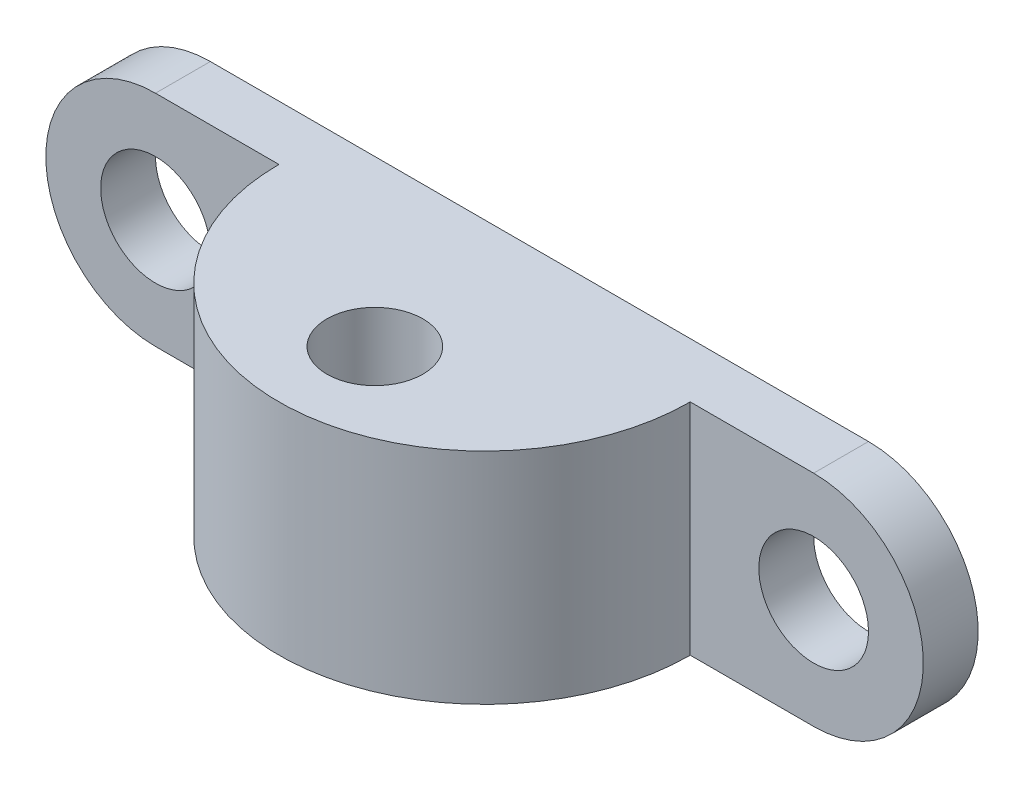
SolidWorks part; units mm, degrees
ref_plane "Front Plane" through (0, 0, 0) normal (0, 0, 1) x (1, 0, 0)
ref_plane "Top Plane" through (0, 0, 0) normal (0, 1, 0) x (1, 0, 0)
ref_plane "Right Plane" through (0, 0, 0) normal (1, 0, 0) x (0, 0, -1)
sketch "Sketch1" plane through (0, 0, 0) normal (0, 0, 1) x (1, 0, 0)
  line L1 (0, 4) -> (24, 4)
  line L2 (0, 4) -> (0, -4)
  line L3 (0, -4) -> (24, -4)
  line L4 (24, 4) -> (24, -4)
  circle A0 centre (0, 0) radius 4
  circle A1 centre (24, 0) radius 4
  dimension "D2" = 8
  dimension "D1" = 24
extrude "Boss-Extrude1" add sketch "Sketch1" along normal blind 2 contours L2 A0 | L2 A0 | A1 L1 A0 L3 | L4 A1 | L4 A1
sketch "Sketch2" plane through (0, -4, 0) normal (0, -1, 0) x (1, 0, 0)
  line L0 (0, 2) -> (24, 2) construction
  line L1 (7.5, 2) -> (16.5, 2)
  line L3 (4.5, 2) -> (19.5, 2)
  line L5 (0, 2) -> (24, 2) construction
  line L6 (7.5, 2) -> (16.5, 2) construction
  line L7 (0, 2) -> (7.5754, 2)
  line L8 (7.5754, 2) -> (22.4246, 2)
  line L9 (22.4246, 2) -> (24, 2)
  line L10 (12, 2) -> (12, 6) construction
  line L11 (0, 0) -> (24, 0) construction
  line L12 (12, 0) -> (12, 2) construction
  arc A0 (19.5, 2) -> (4.5, 2) centre (12, 2) ccw
  circle A1 centre (12, 6) radius 1.75
  point P12 (12, 2)
  point P13 (12, 2)
  dimension "D2" = 15
  dimension "D3" = 3.5
  dimension "D1" = 4
extrude "Boss-Extrude2" add sketch "Sketch2" against normal up to surface (8 mm away)
sketch "Sketch6" plane through (0, 0, 2) normal (0, 0, 1) x (1, 0, 0)
  line L3 (4.5, -4) -> (4.5, 4)
  line L4 (4.5, 4) -> (0, 4)
  line L5 (0, -4) -> (4.5, -4)
  line L7 (4.5, 4) -> (0, 4)
  line L8 (0, -4) -> (4.5, -4)
  line L9 (24, 4) -> (19.5, 4)
  line L10 (19.5, 4) -> (19.5, -4)
  line L11 (19.5, -4) -> (24, -4)
  line L12 (24, 4) -> (19.5, 4)
  line L14 (19.5, -4) -> (24, -4)
  line L15 (4.5, -4) -> (4.5, 4)
  line L16 (19.5, 4) -> (19.5, -4)
  circle A0 centre (0, 0) radius 2
  arc A1 (0, 4) -> (0, -4) centre (0, 0) ccw
  arc A2 (0, 4) -> (0, -4) centre (0, 0) ccw
  arc A3 (24, -4) -> (24, 4) centre (24, 0) ccw
  arc A4 (24, -4) -> (24, 4) centre (24, 0) ccw
  circle A5 centre (24, 0) radius 2
  dimension "D3" = 4
  dimension "D1" = 0
  dimension "D2" = 0
extrude "Cut-Extrude1" cut sketch "Sketch6" against normal through all contours A0 | A5
